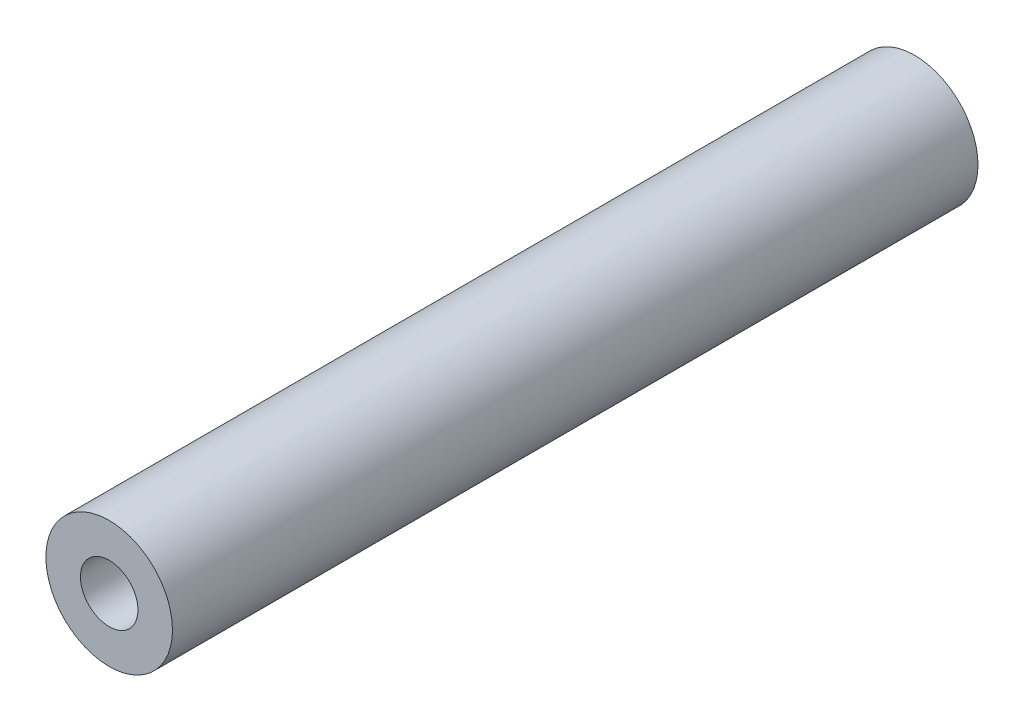
SolidWorks part; units mm, degrees
material "Plastique personnalisé"
ref_plane "Plan de face" through (0, 0, 0) normal (0, 0, 1) x (1, 0, 0)
ref_plane "Plan de dessus" through (0, 0, 0) normal (0, 1, 0) x (1, 0, 0)
ref_plane "Plan de droite" through (0, 0, 0) normal (1, 0, 0) x (0, 0, -1)
sketch "Esquisse1" plane through (0, 0, 0) normal (0, 0, 1) x (1, 0, 0)
  circle A0 centre (0, 0) radius 2.75
  dimension "D1" = 5.5
extrude "Boss.-Extru.1" add sketch "Esquisse1" along normal blind 35
sketch "Esquisse2" plane through (0, 0, 35) normal (0, 0, 1) x (1, 0, 0)
  circle A0 centre (0, 0) radius 1.25
  dimension "D1" = 2.5
extrude "Enlèv. mat.-Extru.1" cut sketch "Esquisse2" against normal up to next
